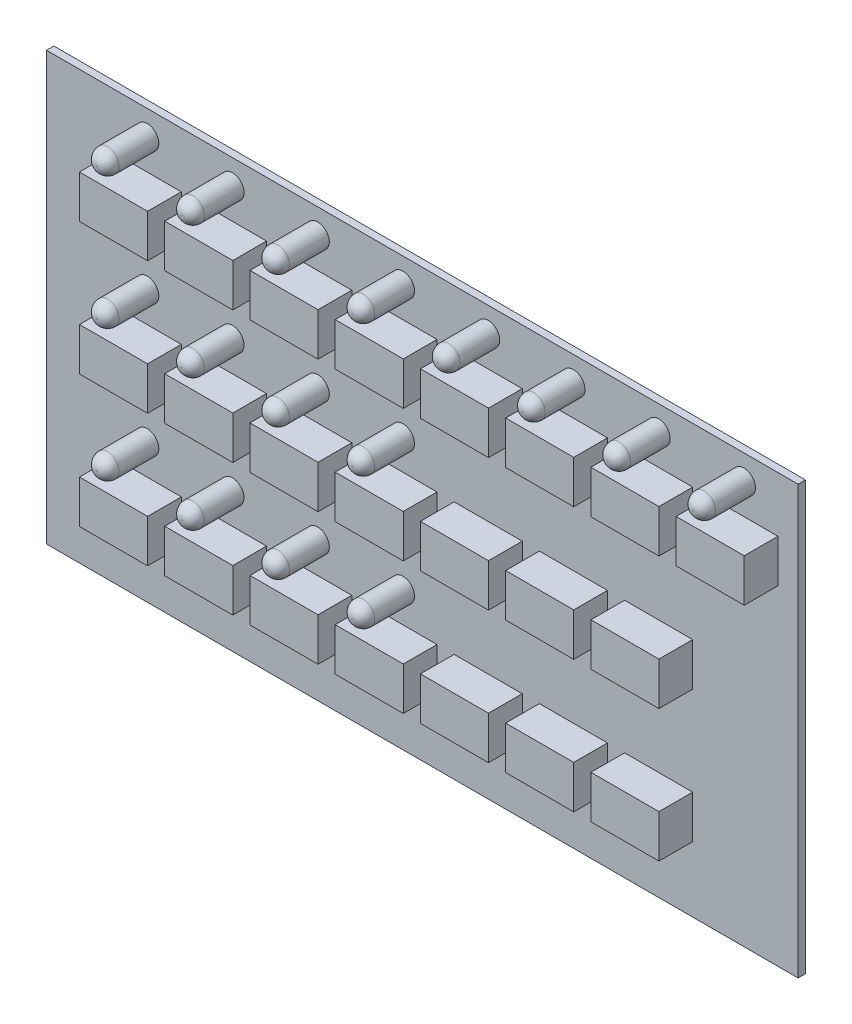
SolidWorks part; units mm, degrees
ref_plane "Front Plane" through (0, 0, 0) normal (0, 0, 1) x (1, 0, 0)
ref_plane "Top Plane" through (0, 0, 0) normal (0, 1, 0) x (1, 0, 0)
ref_plane "Right Plane" through (0, 0, 0) normal (1, 0, 0) x (0, 0, -1)
sketch "Sketch1" plane through (0, 0, 0) normal (0, 0, 1) x (1, 0, 0)
  line L0 (0, 0) -> (0, 92.5068)
  line L1 (0, 92.5068) -> (162.5854, 92.5068)
  line L2 (162.5854, 92.5068) -> (162.5854, 0)
  line L3 (162.5854, 0) -> (0, 0)
extrude "BOARD" add sketch "Sketch1" along normal blind 1.5921 separate body
ref_plane "Plane1" through (0, 0, 1.5921) normal (0, 0, 1) x (1, 0, 0)
sketch "Sketch17" plane through (0, 0, 1.5921) normal (0, 0, 1) x (1, 0, 0)
  circle A0 centre (21.7932, 87.1728) radius 2.5
  dimension "D1" = 5
extrude "LED-KINGBRIGHT_3P_2P54-16" add sketch "Sketch17" along normal blind 11 separate body
fillet "Fillet1" radius 2.4 1 edges at (24.2932, 87.1728, 12.5921)
sketch "Sketch18" plane through (0, 0, 1.5921) normal (0, 0, 1) x (1, 0, 0)
  line L0 (125.0522, 14.1478) -> (125.0522, 23.4188)
  line L1 (125.0522, 23.4188) -> (139.7842, 23.4188)
  line L2 (139.7842, 23.4188) -> (139.7842, 14.1478)
  line L3 (139.7842, 14.1478) -> (125.0522, 14.1478)
extrude "SWITCH-MCDTS2-1" add sketch "Sketch18" along normal blind 7.3 separate body
sketch "Sketch19" plane through (0, 0, 1.5921) normal (0, 0, 1) x (1, 0, 0)
  line L0 (106.6147, 14.1478) -> (106.6147, 23.4188)
  line L1 (106.6147, 23.4188) -> (121.3467, 23.4188)
  line L2 (121.3467, 23.4188) -> (121.3467, 14.1478)
  line L3 (121.3467, 14.1478) -> (106.6147, 14.1478)
extrude "SWITCH-MCDTS2-2" add sketch "Sketch19" along normal blind 7.3 separate body
sketch "Sketch20" plane through (0, 0, 1.5921) normal (0, 0, 1) x (1, 0, 0)
  line L0 (88.1772, 14.1478) -> (88.1772, 23.4188)
  line L1 (88.1772, 23.4188) -> (102.9092, 23.4188)
  line L2 (102.9092, 23.4188) -> (102.9092, 14.1478)
  line L3 (102.9092, 14.1478) -> (88.1772, 14.1478)
extrude "SWITCH-MCDTS2-3" add sketch "Sketch20" along normal blind 7.3 separate body
sketch "Sketch21" plane through (0, 0, 1.5921) normal (0, 0, 1) x (1, 0, 0)
  line L0 (69.7397, 14.1478) -> (69.7397, 23.4188)
  line L1 (69.7397, 23.4188) -> (84.4717, 23.4188)
  line L2 (84.4717, 23.4188) -> (84.4717, 14.1478)
  line L3 (84.4717, 14.1478) -> (69.7397, 14.1478)
extrude "SWITCH-MCDTS2-4" add sketch "Sketch21" along normal blind 7.3 separate body
sketch "Sketch22" plane through (0, 0, 1.5921) normal (0, 0, 1) x (1, 0, 0)
  line L0 (51.3022, 14.1478) -> (51.3022, 23.4188)
  line L1 (51.3022, 23.4188) -> (66.0342, 23.4188)
  line L2 (66.0342, 23.4188) -> (66.0342, 14.1478)
  line L3 (66.0342, 14.1478) -> (51.3022, 14.1478)
extrude "SWITCH-MCDTS2-5" add sketch "Sketch22" along normal blind 7.3 separate body
sketch "Sketch23" plane through (0, 0, 1.5921) normal (0, 0, 1) x (1, 0, 0)
  line L0 (32.8647, 14.1478) -> (32.8647, 23.4188)
  line L1 (32.8647, 23.4188) -> (47.5967, 23.4188)
  line L2 (47.5967, 23.4188) -> (47.5967, 14.1478)
  line L3 (47.5967, 14.1478) -> (32.8647, 14.1478)
extrude "SWITCH-MCDTS2-6" add sketch "Sketch23" along normal blind 7.3 separate body
sketch "Sketch24" plane through (0, 0, 1.5921) normal (0, 0, 1) x (1, 0, 0)
  line L0 (14.4272, 14.1478) -> (14.4272, 23.4188)
  line L1 (14.4272, 23.4188) -> (29.1592, 23.4188)
  line L2 (29.1592, 23.4188) -> (29.1592, 14.1478)
  line L3 (29.1592, 14.1478) -> (14.4272, 14.1478)
extrude "SWITCH-MCDTS2-7" add sketch "Sketch24" along normal blind 7.3 separate body
sketch "Sketch25" plane through (0, 0, 1.5921) normal (0, 0, 1) x (1, 0, 0)
  line L0 (125.0522, 42.7228) -> (125.0522, 51.9938)
  line L1 (125.0522, 51.9938) -> (139.7842, 51.9938)
  line L2 (139.7842, 51.9938) -> (139.7842, 42.7228)
  line L3 (139.7842, 42.7228) -> (125.0522, 42.7228)
extrude "SWITCH-MCDTS2-8" add sketch "Sketch25" along normal blind 7.3 separate body
sketch "Sketch26" plane through (0, 0, 1.5921) normal (0, 0, 1) x (1, 0, 0)
  line L0 (106.6147, 42.7228) -> (106.6147, 51.9938)
  line L1 (106.6147, 51.9938) -> (121.3467, 51.9938)
  line L2 (121.3467, 51.9938) -> (121.3467, 42.7228)
  line L3 (121.3467, 42.7228) -> (106.6147, 42.7228)
extrude "SWITCH-MCDTS2-9" add sketch "Sketch26" along normal blind 7.3 separate body
sketch "Sketch27" plane through (0, 0, 1.5921) normal (0, 0, 1) x (1, 0, 0)
  line L0 (88.1772, 42.7228) -> (88.1772, 51.9938)
  line L1 (88.1772, 51.9938) -> (102.9092, 51.9938)
  line L2 (102.9092, 51.9938) -> (102.9092, 42.7228)
  line L3 (102.9092, 42.7228) -> (88.1772, 42.7228)
extrude "SWITCH-MCDTS2-10" add sketch "Sketch27" along normal blind 7.3 separate body
sketch "Sketch28" plane through (0, 0, 1.5921) normal (0, 0, 1) x (1, 0, 0)
  line L0 (69.7397, 42.7228) -> (69.7397, 51.9938)
  line L1 (69.7397, 51.9938) -> (84.4717, 51.9938)
  line L2 (84.4717, 51.9938) -> (84.4717, 42.7228)
  line L3 (84.4717, 42.7228) -> (69.7397, 42.7228)
extrude "SWITCH-MCDTS2-11" add sketch "Sketch28" along normal blind 7.3 separate body
sketch "Sketch29" plane through (0, 0, 1.5921) normal (0, 0, 1) x (1, 0, 0)
  line L0 (51.3022, 42.7228) -> (51.3022, 51.9938)
  line L1 (51.3022, 51.9938) -> (66.0342, 51.9938)
  line L2 (66.0342, 51.9938) -> (66.0342, 42.7228)
  line L3 (66.0342, 42.7228) -> (51.3022, 42.7228)
extrude "SWITCH-MCDTS2-12" add sketch "Sketch29" along normal blind 7.3 separate body
sketch "Sketch30" plane through (0, 0, 1.5921) normal (0, 0, 1) x (1, 0, 0)
  line L0 (32.8647, 42.7228) -> (32.8647, 51.9938)
  line L1 (32.8647, 51.9938) -> (47.5967, 51.9938)
  line L2 (47.5967, 51.9938) -> (47.5967, 42.7228)
  line L3 (47.5967, 42.7228) -> (32.8647, 42.7228)
extrude "SWITCH-MCDTS2-13" add sketch "Sketch30" along normal blind 7.3 separate body
sketch "Sketch31" plane through (0, 0, 1.5921) normal (0, 0, 1) x (1, 0, 0)
  line L0 (14.4272, 42.7228) -> (14.4272, 51.9938)
  line L1 (14.4272, 51.9938) -> (29.1592, 51.9938)
  line L2 (29.1592, 51.9938) -> (29.1592, 42.7228)
  line L3 (29.1592, 42.7228) -> (14.4272, 42.7228)
extrude "SWITCH-MCDTS2-14" add sketch "Sketch31" along normal blind 7.3 separate body
sketch "Sketch32" plane through (0, 0, 1.5921) normal (0, 0, 1) x (1, 0, 0)
  line L0 (143.4897, 71.2978) -> (143.4897, 80.5688)
  line L1 (143.4897, 80.5688) -> (158.2217, 80.5688)
  line L2 (158.2217, 80.5688) -> (158.2217, 71.2978)
  line L3 (158.2217, 71.2978) -> (143.4897, 71.2978)
extrude "SWITCH-MCDTS2-15" add sketch "Sketch32" along normal blind 7.3 separate body
sketch "Sketch33" plane through (0, 0, 1.5921) normal (0, 0, 1) x (1, 0, 0)
  line L0 (125.0522, 71.2978) -> (125.0522, 80.5688)
  line L1 (125.0522, 80.5688) -> (139.7842, 80.5688)
  line L2 (139.7842, 80.5688) -> (139.7842, 71.2978)
  line L3 (139.7842, 71.2978) -> (125.0522, 71.2978)
extrude "SWITCH-MCDTS2-16" add sketch "Sketch33" along normal blind 7.3 separate body
sketch "Sketch34" plane through (0, 0, 1.5921) normal (0, 0, 1) x (1, 0, 0)
  line L0 (106.6147, 71.2978) -> (106.6147, 80.5688)
  line L1 (106.6147, 80.5688) -> (121.3467, 80.5688)
  line L2 (121.3467, 80.5688) -> (121.3467, 71.2978)
  line L3 (121.3467, 71.2978) -> (106.6147, 71.2978)
extrude "SWITCH-MCDTS2-17" add sketch "Sketch34" along normal blind 7.3 separate body
sketch "Sketch35" plane through (0, 0, 1.5921) normal (0, 0, 1) x (1, 0, 0)
  line L0 (88.1772, 71.2978) -> (88.1772, 80.5688)
  line L1 (88.1772, 80.5688) -> (102.9092, 80.5688)
  line L2 (102.9092, 80.5688) -> (102.9092, 71.2978)
  line L3 (102.9092, 71.2978) -> (88.1772, 71.2978)
extrude "SWITCH-MCDTS2-18" add sketch "Sketch35" along normal blind 7.3 separate body
sketch "Sketch36" plane through (0, 0, 1.5921) normal (0, 0, 1) x (1, 0, 0)
  line L0 (69.7397, 71.2978) -> (69.7397, 80.5688)
  line L1 (69.7397, 80.5688) -> (84.4717, 80.5688)
  line L2 (84.4717, 80.5688) -> (84.4717, 71.2978)
  line L3 (84.4717, 71.2978) -> (69.7397, 71.2978)
extrude "SWITCH-MCDTS2-19" add sketch "Sketch36" along normal blind 7.3 separate body
sketch "Sketch37" plane through (0, 0, 1.5921) normal (0, 0, 1) x (1, 0, 0)
  line L0 (51.3022, 71.2978) -> (51.3022, 80.5688)
  line L1 (51.3022, 80.5688) -> (66.0342, 80.5688)
  line L2 (66.0342, 80.5688) -> (66.0342, 71.2978)
  line L3 (66.0342, 71.2978) -> (51.3022, 71.2978)
extrude "SWITCH-MCDTS2-20" add sketch "Sketch37" along normal blind 7.3 separate body
sketch "Sketch38" plane through (0, 0, 1.5921) normal (0, 0, 1) x (1, 0, 0)
  line L0 (32.8647, 71.2978) -> (32.8647, 80.5688)
  line L1 (32.8647, 80.5688) -> (47.5967, 80.5688)
  line L2 (47.5967, 80.5688) -> (47.5967, 71.2978)
  line L3 (47.5967, 71.2978) -> (32.8647, 71.2978)
extrude "SWITCH-MCDTS2-21" add sketch "Sketch38" along normal blind 7.3 separate body
sketch "Sketch39" plane through (0, 0, 1.5921) normal (0, 0, 1) x (1, 0, 0)
  line L0 (14.4272, 71.2978) -> (14.4272, 80.5688)
  line L1 (14.4272, 80.5688) -> (29.1592, 80.5688)
  line L2 (29.1592, 80.5688) -> (29.1592, 71.2978)
  line L3 (29.1592, 71.2978) -> (14.4272, 71.2978)
extrude "SWITCH-MCDTS2-22" add sketch "Sketch39" along normal blind 7.3 separate body
pattern_linear "LPattern1" count 8 spacing 18.4375 along (1, 0, 0) count 3 spacing 28.575 along (0, -1, 0) skipping (4, 1), (4, 2), (5, 1), (5, 2), (6, 1), (6, 2), (7, 1), (7, 2) of "LED-KINGBRIGHT_3P_2P54-16", "Fillet1"
